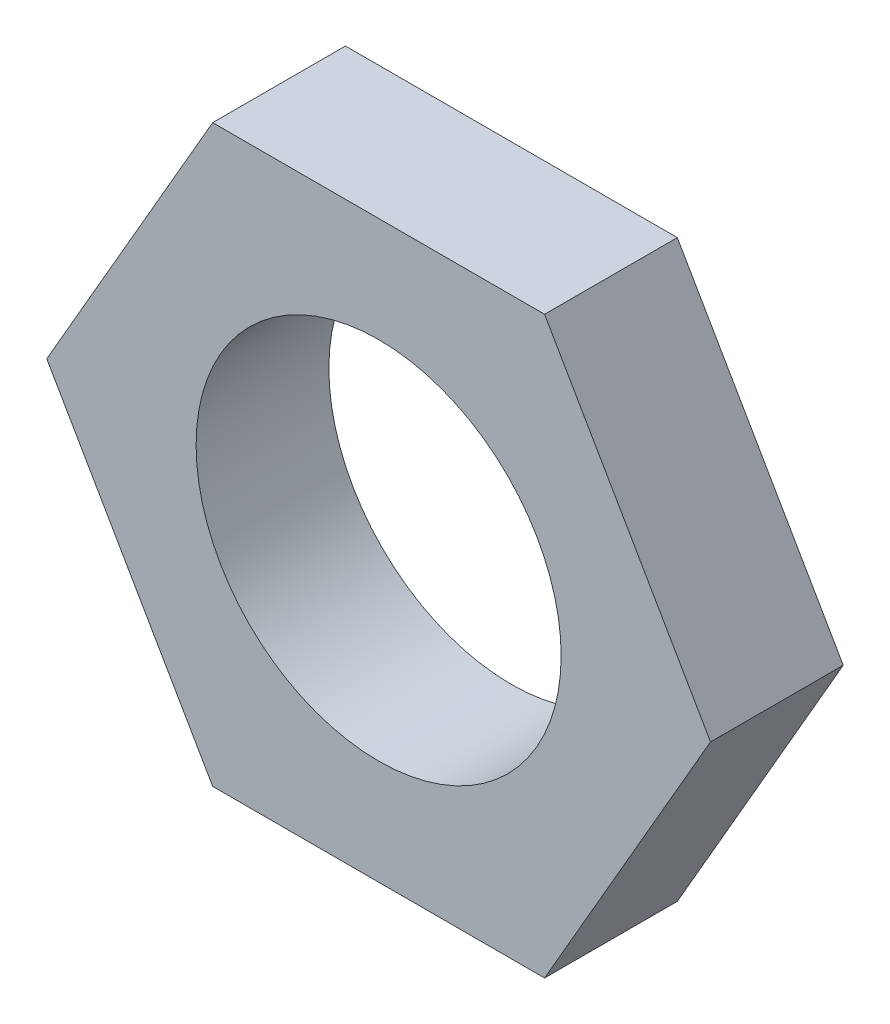
SolidWorks part; units mm, degrees
ref_plane "Front Plane" through (0, 0, 0) normal (0, 0, 1) x (1, 0, 0)
ref_plane "Top Plane" through (0, 0, 0) normal (0, 1, 0) x (1, 0, 0)
ref_plane "Right Plane" through (0, 0, 0) normal (1, 0, 0) x (0, 0, -1)
sketch "Sketch1" plane through (0, 0, 0) normal (0, 0, 1) x (1, 0, 0)
  line L1 (-2.5, -4.3301) -> (2.5, -4.3301)
  line L2 (2.5, -4.3301) -> (5, 0)
  line L3 (5, 0) -> (2.5, 4.3301)
  line L4 (2.5, 4.3301) -> (-2.5, 4.3301)
  line L5 (-2.5, 4.3301) -> (-5, 0)
  line L6 (-5, 0) -> (-2.5, -4.3301)
  circle A0 centre (0, 0) radius 4.3301 construction
  dimension "D1" = 5
  dimension "D2" = 5
extrude "Boss-Extrude1" add sketch "Sketch1" along normal blind 2
sketch "Sketch3" plane through (0, 0, 0) normal (0, 0, -1) x (-1, 0, 0)
  circle A0 centre (0, 0) radius 2.75
  dimension "D1" = 5.5
extrude "Cut-Extrude1" cut sketch "Sketch3" against normal through all
sketch "Sketch2" plane through (0, 0, 2) normal (0, 0, 1) x (1, 0, 0)
  circle A0 centre (0, 0) radius 2.5
  dimension "D1" = 5
